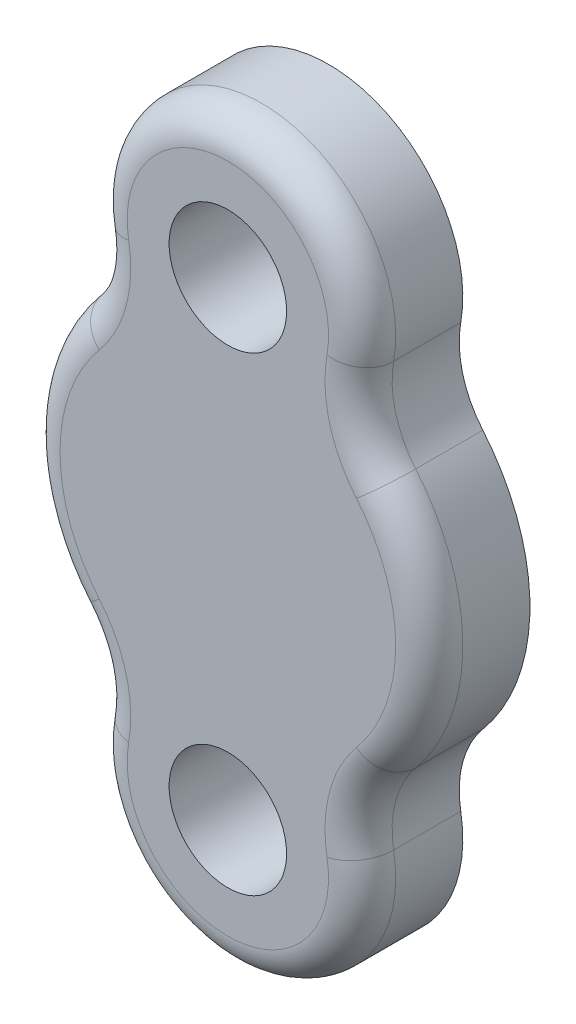
SolidWorks part; units mm, degrees
ref_plane "Front Plane" through (0, 0, 0) normal (0, 0, 1) x (1, 0, 0)
ref_plane "Top Plane" through (0, 0, 0) normal (0, 1, 0) x (1, 0, 0)
ref_plane "Right Plane" through (0, 0, 0) normal (1, 0, 0) x (0, 0, -1)
sketch "Sketch1" plane through (0, 0, 0) normal (0, 0, 1) x (1, 0, 0)
  arc A0 (-110.7959, 3.0072) -> (-110.7959, -4.7071) centre (-106.2, -0.85) ccw
  circle A1 centre (-106.2, -0.85) radius 4.05 construction
  arc A2 (-102.2607, 5.4561) -> (-110.1394, 5.4561) centre (-106.2, 6.15) ccw
  arc A3 (-110.1394, -7.1561) -> (-102.2607, -7.1561) centre (-106.2, -7.85) ccw
  circle A4 centre (-106.2, -7.85) radius 1.4 construction
  circle A5 centre (-106.2, 6.15) radius 1.4 construction
  arc A6 (-101.6041, -4.7071) -> (-101.6041, 3.0072) centre (-106.2, -0.85) ccw
  circle A7 centre (-106.2, 6.15) radius 1.75
  circle A8 centre (-106.2, -7.85) radius 1.75
  arc A9 (-110.7959, -4.7071) -> (-110.1394, -7.1561) centre (-113.0939, -6.6357) cw
  arc A10 (-101.6041, -4.7071) -> (-102.2607, -7.1561) centre (-99.3061, -6.6357) ccw
  arc A11 (-102.2607, 5.4561) -> (-101.6041, 3.0072) centre (-99.3061, 4.9357) ccw
  arc A12 (-110.1394, 5.4561) -> (-110.7959, 3.0072) centre (-113.0939, 4.9357) cw
  point P20 (-102.7781, -5.7786)
  dimension "D1" = 12
  dimension "D2" = 8
  dimension "D3" = 3.5
  dimension "D4" = 3
extrude "Boss-Extrude1" add sketch "Sketch1" along normal blind 3
fillet "Fillet1" radius 1 8 edges at (-106.2, -11.85, 3) (-106.2, 10.15, 3) (-112.2, -0.85, 3) (-100.2, -0.85, 3) (-102.2038, -5.8589, 3) (-110.1962, -5.8589, 3) (-110.1962, 4.1589, 3) (-102.2038, 4.1589, 3)
